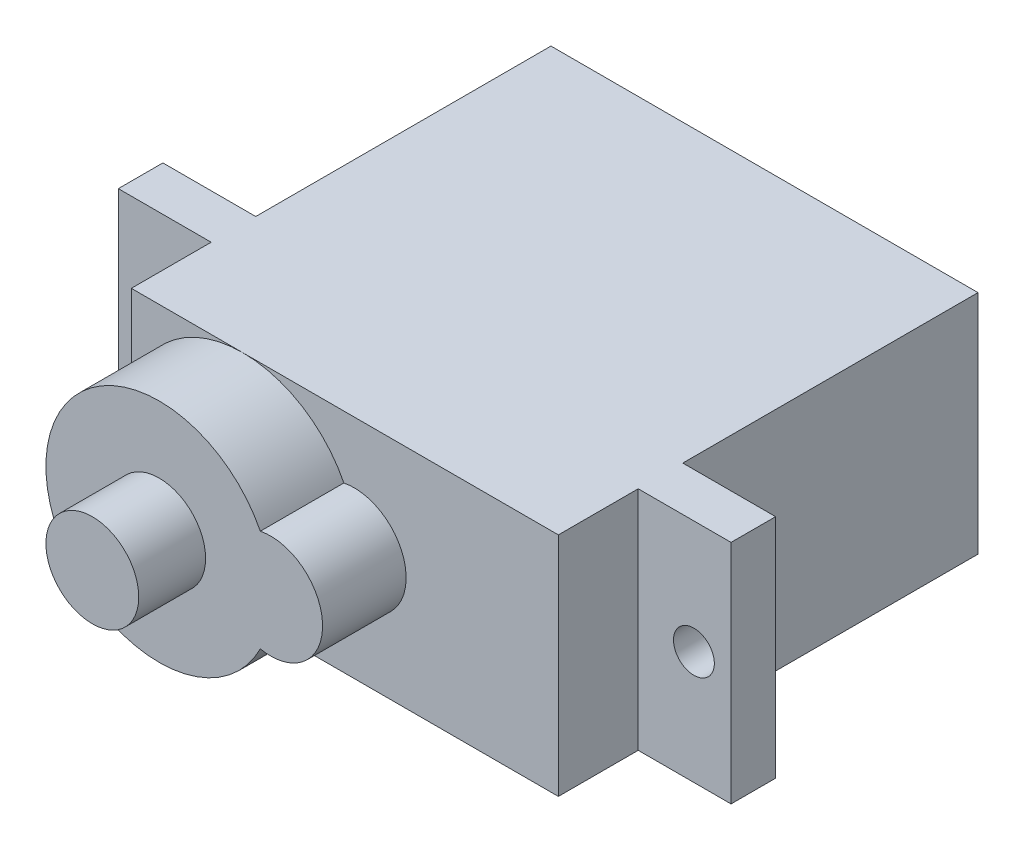
SolidWorks part; units mm, degrees
ref_plane "Front Plane" through (0, 0, 0) normal (0, 0, 1) x (1, 0, 0)
ref_plane "Top Plane" through (0, 0, 0) normal (0, 1, 0) x (1, 0, 0)
ref_plane "Right Plane" through (0, 0, 0) normal (1, 0, 0) x (0, 0, -1)
sketch "Case_conservative_plan_23x12p2_profile" plane through (0, 0, 0) normal (0, 0, 1) x (1, 0, 0)
  line L1 (-6, -6.1) -> (17, -6.1)
  line L2 (-6, -6.1) -> (-6, 6.1)
  line L3 (-6, 6.1) -> (17, 6.1)
  line L4 (17, -6.1) -> (17, 6.1)
  dimension "D1" = 23
  dimension "D2" = 12.2
extrude "Case_conservative_plan_23x12p2" add sketch "Case_conservative_plan_23x12p2_profile" along normal blind 22.6 from offset 18.3
sketch "Mounting_ears_33x12p2_profile" plane through (0, 0, 0) normal (0, 0, 1) x (1, 0, 0)
  line L1 (-11, -6.1) -> (22, -6.1)
  line L2 (-11, -6.1) -> (-11, 6.1)
  line L3 (-11, 6.1) -> (22, 6.1)
  line L4 (22, -6.1) -> (22, 6.1)
  dimension "D1" = 33
  dimension "D2" = 12.2
extrude "Mounting_ears_33x12p2" add sketch "Mounting_ears_33x12p2_profile" along normal blind 2.4 from offset 2.4
sketch "Raised_gear_cover_envelope_profile" plane through (0, 0, 0) normal (0, 0, 1) x (1, 0, 0)
  circle A0 centre (0, 0) radius 6.1
  dimension "D1" = 12.2
extrude "Raised_gear_cover_envelope" add sketch "Raised_gear_cover_envelope_profile" along normal blind 4.5 from offset 4.3
sketch "Secondary_gear_cover_envelope_profile" plane through (0, 0, 0) normal (0, 0, 1) x (1, 0, 0)
  circle A0 centre (6, 0) radius 2.8
  dimension "D1" = 5.6
extrude "Secondary_gear_cover_envelope" add sketch "Secondary_gear_cover_envelope_profile" along normal blind 4.5 from offset 4.3
sketch "Output_envelope_not_spline_profile" plane through (0, 0, 0) normal (0, 0, 1) x (1, 0, 0)
  circle A0 centre (0, 0) radius 2.5
  dimension "D1" = 5
extrude "Output_envelope_not_spline" add sketch "Output_envelope_not_spline_profile" along normal blind 3.6 from offset 8.8
sketch "Mounting_holes_nominal_profile" plane through (0, 0, 0) normal (0, 0, 1) x (1, 0, 0)
  circle A0 centre (-9, 0) radius 1.1
  circle A1 centre (20, 0) radius 1.1
  dimension "D1" = 2.2
  dimension "D2" = 2.2
extrude "Mounting_holes_nominal" cut sketch "Mounting_holes_nominal_profile" along normal through all from offset 50
